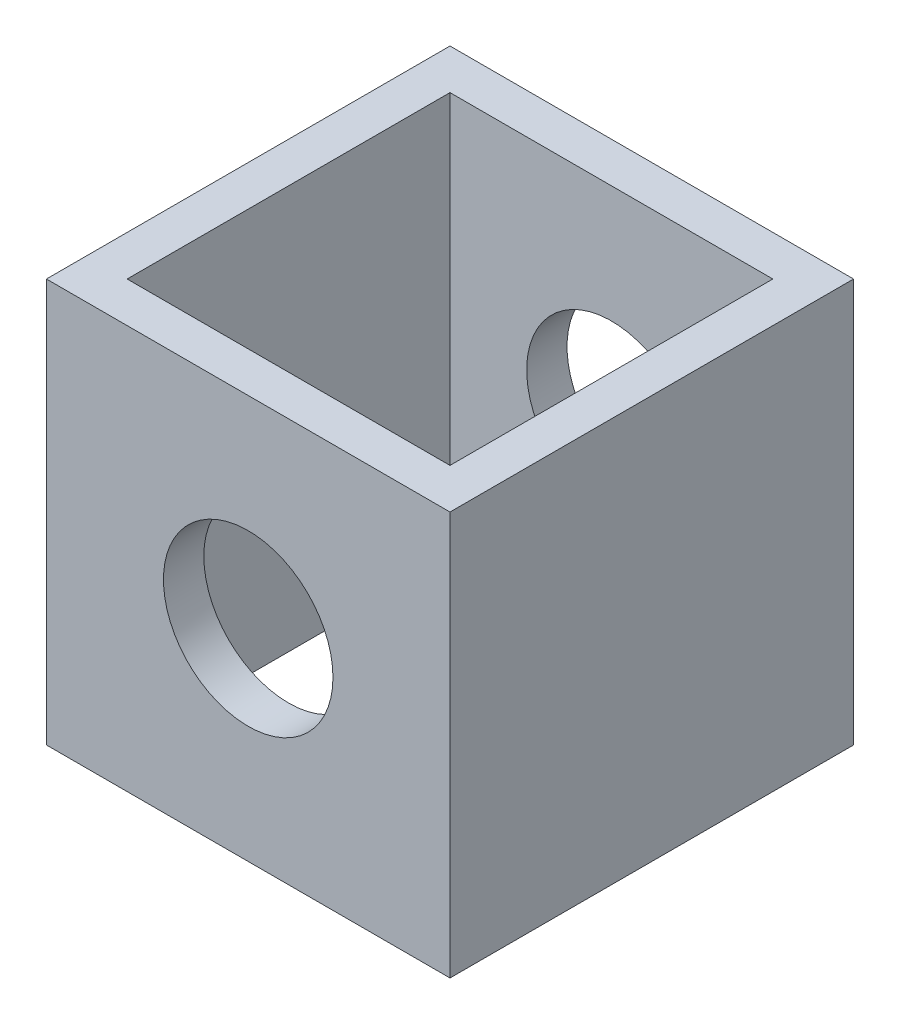
SolidWorks part; units mm, degrees
material "5052-H34"
ref_plane "正面" through (0, 0, 0) normal (0, 0, 1) x (1, 0, 0)
ref_plane "平面" through (0, 0, 0) normal (0, 1, 0) x (1, 0, 0)
ref_plane "右側面" through (0, 0, 0) normal (1, 0, 0) x (0, 0, -1)
sketch "ｽｹｯﾁ1" plane through (0, 0, 0) normal (0, 1, 0) x (1, 0, 0)
  line L1 (-5, 5) -> (5, 5)
  line L2 (-5, 5) -> (-5, -5)
  line L3 (-5, -5) -> (5, -5)
  line L4 (5, 5) -> (5, -5)
  line L5 (-5, 5) -> (5, -5) construction
  line L6 (-5, -5) -> (5, 5) construction
  point P0 (0, 0)
  dimension "D1" = 10
extrude "押し出し-薄板1" add sketch "ｽｹｯﾁ1" along normal blind 10 thin
sketch "ｽｹｯﾁ2" plane through (0, 0, 5) normal (0, 0, 1) x (1, 0, 0)
  line L0 (0, 10) -> (0, 0) construction
  line L1 (-5, 10) -> (5, 10) construction
  circle A0 centre (0, 5) radius 2.1
  dimension "D1" = 4.2
extrude "ｶｯﾄ - 押し出し1" cut sketch "ｽｹｯﾁ2" against normal through all
